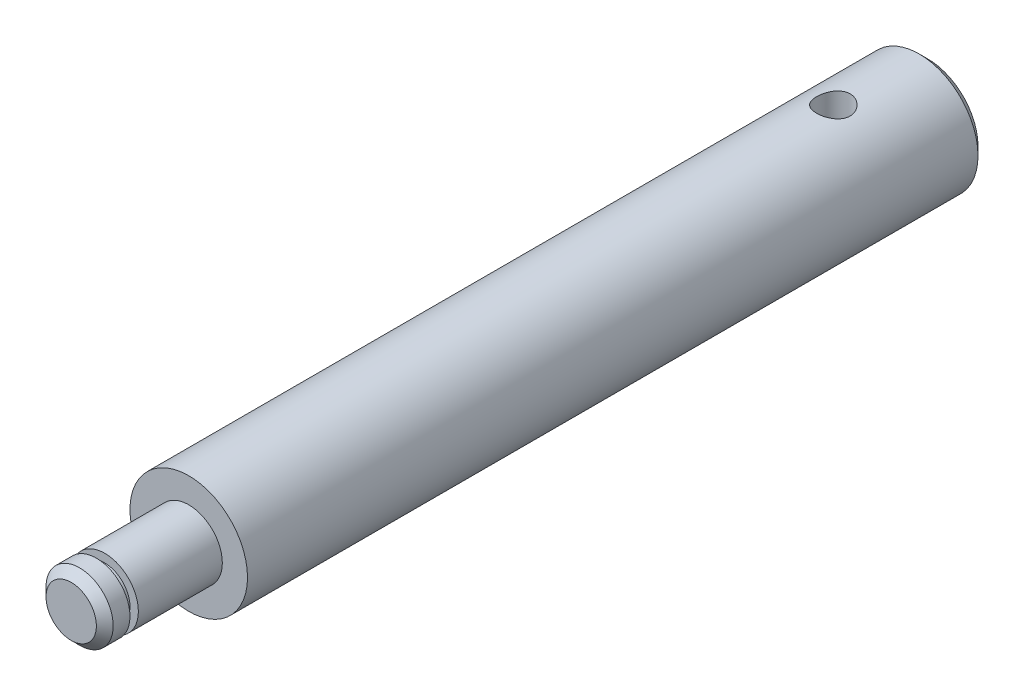
SolidWorks part; units mm, degrees
material "Alliage de zinc AC41A, brut"
ref_plane "Plan de face" through (0, 0, 0) normal (0, 0, 1) x (1, 0, 0)
ref_plane "Plan de dessus" through (0, 0, 0) normal (0, 1, 0) x (1, 0, 0)
ref_plane "Plan de droite" through (0, 0, 0) normal (1, 0, 0) x (0, 0, -1)
sketch "Esquisse1" plane through (0, 0, 0) normal (0, 0, 1) x (1, 0, 0)
  circle A0 centre (0, 0) radius 3.5
  dimension "D1" = 7
extrude "Boss.-Extru.1" add sketch "Esquisse1" along normal blind 44
sketch "Esquisse2" plane through (0, 0, 44) normal (0, 0, 1) x (1, 0, 0)
  circle A0 centre (0, 0) radius 2
  dimension "D1" = 4
extrude "Boss.-Extru.2" add sketch "Esquisse2" along normal blind 5
sketch "Esquisse3" plane through (0, 0, 49) normal (0, 0, 1) x (1, 0, 0)
  circle A0 centre (0, 0) radius 1.5
  dimension "D1" = 3
extrude "Boss.-Extru.3" add sketch "Esquisse3" along normal blind 0.5
sketch "Esquisse4" plane through (0, 0, 49.5) normal (0, 0, 1) x (1, 0, 0)
  circle A0 centre (0, 0) radius 2
  dimension "D1" = 4
extrude "Boss.-Extru.4" add sketch "Esquisse4" along normal blind 1.5
chamfer "Chanfrein1" distance 0.5 angle 45 1 edges at (2, 0, 51)
chamfer "Chanfrein2" distance 0.5 angle 45 1 edges at (3.5, 0, 0)
hole_wizard "Diamètre du perçage Ø2.0 (2)3" positions "Esquisse3D1" profile "Esquisse12" hole size "Ø2.0" standard "ISO" end condition through all
sketch3d "Esquisse3D1"
  line L0 (0, 0, 0) -> (0, 0, 5.615) construction
  line L2 (0, 3.5, 5.615) -> (0, 0, 5.615) construction
  point P0 (0, 3.5, 5.615)
  dimension "D1" = 5.615
sketch "Esquisse12" plane through (0, 3.5, 5.615) normal (1, 0, 0) x (0, 0, 1)
  line L0 (0, 0) -> (0, 7)
  line L1 (0, 7) -> (1, 7)
  line L2 (1, 7) -> (1, 0)
  line L5 (1, 0) -> (0, 0)
  line L11 (0, -6.35) -> (0, 107.95) construction
  dimension "Diamètre du perçage jusqu'au prochain" = 2
  dimension "Profondeur du perçage jusqu'au prochain" = 7
cosmetic thread "Représentation de filetage1" parameters "D2"=3
